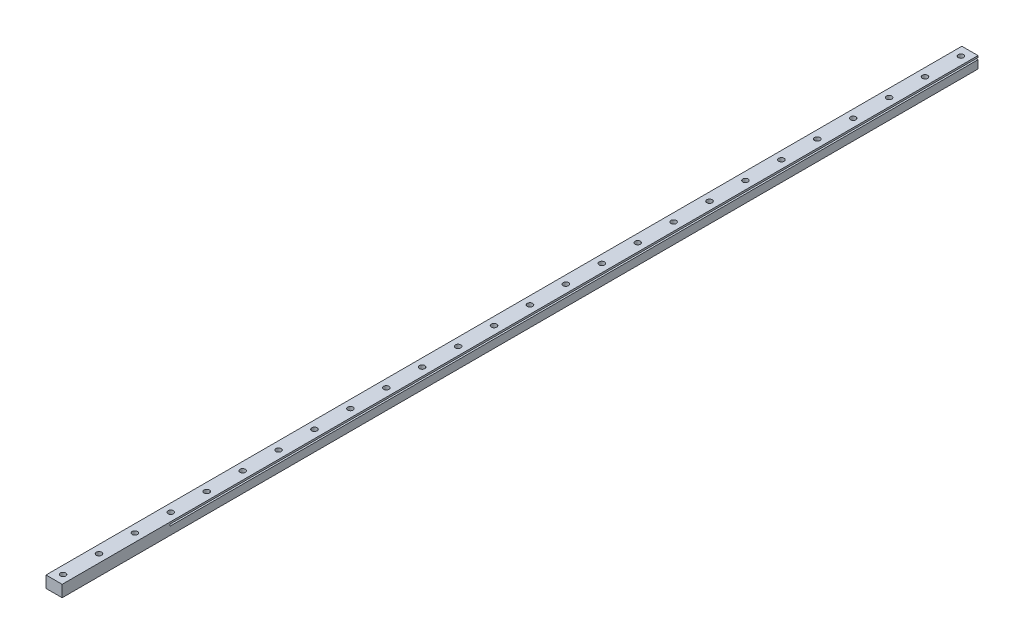
SolidWorks part; units mm, degrees
ref_plane "前视基准面" through (0, 0, 0) normal (0, 0, 1) x (1, 0, 0)
ref_plane "上视基准面" through (0, 0, 0) normal (0, 1, 0) x (1, 0, 0)
ref_plane "右视基准面" through (0, 0, 0) normal (1, 0, 0) x (0, 0, -1)
other "Configuration Table"
sketch "草图1" plane through (0, 0, 0) normal (0, 0, 1) x (1, 0, 0)
  line L1 (0, 0) -> (-9, 0)
  line L2 (0, 0) -> (0, 6.5)
  line L3 (0, 6.5) -> (-9, 6.5)
  line L4 (-9, 0) -> (-9, 6.5)
  dimension "D1" = 9
  dimension "D2" = 6.5
extrude "凸台-拉伸1" add sketch "草图1" along normal blind 510
sketch "草图2" plane through (0, 0, 0) normal (0, 0, -1) x (-1, 0, 0)
  line L0 (0, 6.5) -> (0, 5.5) construction
  line L1 (0, 0) -> (0, 6.5) construction
  line L2 (2, 5.5) -> (0, 5.5)
  line L3 (2, 4.5) -> (0, 4.5)
  line L4 (0, 4.5) -> (0, 5.5)
  line L5 (2, 5.5) -> (2, 4.5)
  line L6 (4.5, 6.5) -> (4.5, 5.0177) construction
  line L7 (0, 6.5) -> (9, 6.5) construction
  line L8 (7, 5.5) -> (9, 5.5)
  line L9 (9, 4.5) -> (9, 5.5)
  line L10 (7, 4.5) -> (9, 4.5)
  line L11 (7, 5.5) -> (7, 4.5)
  dimension "D1" = 1
  dimension "D2" = 1
  dimension "D3" = 2
extrude "切除-拉伸1" cut sketch "草图2" against normal blind 450
sketch "草图3" plane through (0, 6.5, 0) normal (0, 1, 0) x (1, 0, 0)
  line L0 (-4.5, 0) -> (-4.5, -5) construction
  line L1 (0, 0) -> (-9, 0) construction
  circle A0 centre (-4.5, -5) radius 1.5
  circle A1 centre (-4.5, -25) radius 1.5
  circle A2 centre (-4.5, -45) radius 1.5
  circle A3 centre (-4.5, -65) radius 1.5
  circle A4 centre (-4.5, -85) radius 1.5
  circle A5 centre (-4.5, -105) radius 1.5
  circle A6 centre (-4.5, -125) radius 1.5
  circle A7 centre (-4.5, -145) radius 1.5
  circle A8 centre (-4.5, -165) radius 1.5
  circle A9 centre (-4.5, -185) radius 1.5
  circle A10 centre (-4.5, -205) radius 1.5
  circle A11 centre (-4.5, -225) radius 1.5
  circle A12 centre (-4.5, -245) radius 1.5
  circle A13 centre (-4.5, -265) radius 1.5
  circle A14 centre (-4.5, -285) radius 1.5
  circle A15 centre (-4.5, -305) radius 1.5
  circle A16 centre (-4.5, -325) radius 1.5
  circle A17 centre (-4.5, -345) radius 1.5
  circle A18 centre (-4.5, -365) radius 1.5
  circle A19 centre (-4.5, -385) radius 1.5
  circle A20 centre (-4.5, -405) radius 1.5
  circle A21 centre (-4.5, -425) radius 1.5
  circle A22 centre (-4.5, -445) radius 1.5
  circle A23 centre (-4.5, -465) radius 1.5
  circle A24 centre (-4.5, -485) radius 1.5
  circle A25 centre (-4.5, -505) radius 1.5
  dimension "D2" = 3
  dimension "D1" = 5
  dimension "D3" = 23
  dimension "D4" = 4
extrude "切除-拉伸2" cut sketch "草图3" against normal up to next (6.5 mm away)
